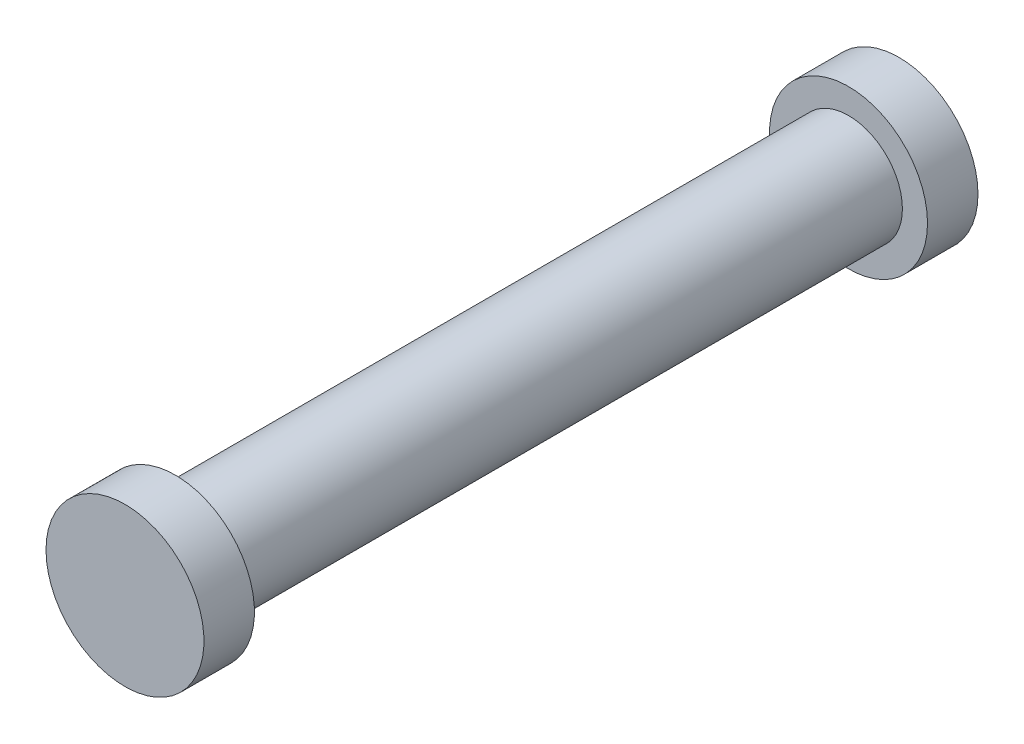
SolidWorks part; units mm, degrees
ref_plane "Front Plane" through (0, 0, 0) normal (0, 0, 1) x (1, 0, 0)
ref_plane "Top Plane" through (0, 0, 0) normal (0, 1, 0) x (1, 0, 0)
ref_plane "Right Plane" through (0, 0, 0) normal (1, 0, 0) x (0, 0, -1)
sketch "Sketch1" plane through (0, 0, 0) normal (0, 0, 1) x (1, 0, 0)
  circle A0 centre (0, 0) radius 4.064
  dimension "D1" = 8.128
extrude "Boss-Extrude1" add sketch "Sketch1" along normal blind 50.8
sketch "Sketch2" plane through (0, 0, 50.8) normal (0, 0, 1) x (1, 0, 0)
  circle A0 centre (0, 0) radius 5.9605
extrude "Boss-Extrude2" add sketch "Sketch2" along normal blind 3.81
sketch "Sketch3" plane through (0, 0, 0) normal (0, 0, -1) x (-1, 0, 0)
  circle A0 centre (0, 0) radius 5.9605
extrude "Boss-Extrude3" add sketch "Sketch3" along normal blind 3.81
